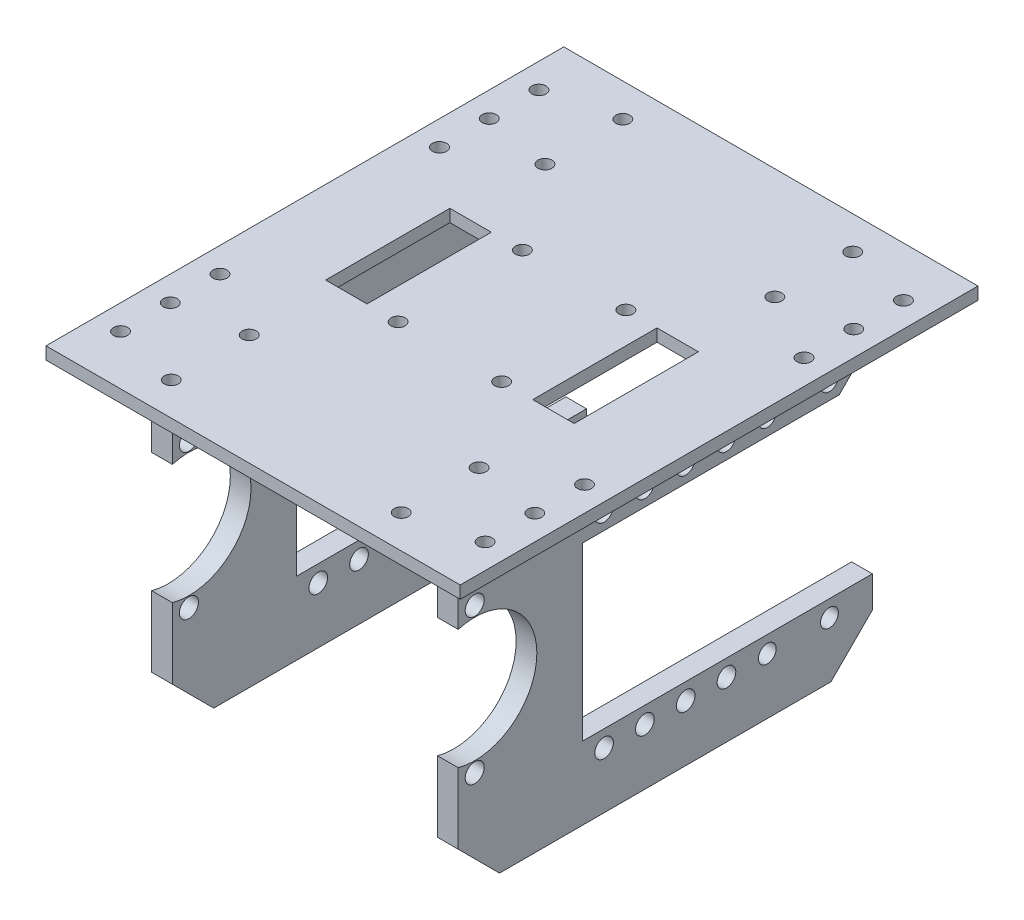
SolidWorks part; units mm, degrees
ref_plane "前视基准面" through (0, 0, 0) normal (0, 0, 1) x (1, 0, 0)
ref_plane "上视基准面" through (0, 0, 0) normal (0, 1, 0) x (1, 0, 0)
ref_plane "右视基准面" through (0, 0, 0) normal (1, 0, 0) x (0, 0, -1)
sketch "草图1" plane through (0, 0, 0) normal (0, 1, 0) x (1, 0, 0)
  line L1 (-50, -62.5) -> (50, -62.5)
  line L2 (-50, -62.5) -> (-50, 62.5)
  line L3 (-50, 62.5) -> (50, 62.5)
  line L4 (50, -62.5) -> (50, 62.5)
  line L5 (-50, -62.5) -> (50, 62.5) construction
  line L6 (-50, 62.5) -> (50, -62.5) construction
  point P0 (0, 0)
  dimension "D1" = 100
  dimension "D2" = 125
extrude "凸台-拉伸1" add sketch "草图1" along normal blind 3
sketch "草图2" plane through (0, 0, 0) normal (0, -1, 0) x (1, 0, 0)
  line L5 (0, -1.65) -> (0, 1.65) construction
  line L6 (-37, -50) -> (-32, -50)
  line L7 (-37, -50) -> (-37, 50)
  line L8 (-37, 50) -> (-32, 50)
  line L13 (-32, -50) -> (-32, 50)
  line L14 (-37, -50) -> (-32, 50) construction
  line L15 (-37, 50) -> (-32, -50) construction
  line L16 (37, 50) -> (32, -50) construction
  line L17 (37, -50) -> (32, 50) construction
  line L18 (32, -50) -> (32, 50)
  line L19 (37, 50) -> (32, 50)
  line L20 (37, -50) -> (37, 50)
  line L21 (37, -50) -> (32, -50)
  point P0 (-34.5, 0)
  point P11 (34.5, 0)
  dimension "D1" = 5
  dimension "D2" = 64
  dimension "D3" = 100
extrude "凸台-拉伸2" add sketch "草图2" along normal blind 75
sketch "草图3" plane through (-37, 0, 0) normal (-1, 0, 0) x (0, 0, 1)
  line L0 (0, -42.9) -> (0, 42.9) construction
  line L1 (50, 0) -> (-50, 0) construction
  line L2 (4.925, -12) -> (4.925, -61.42) construction
  line L3 (4.925, -36.71) -> (59.1857, -36.71) construction
  circle A0 centre (-4.925, -12) radius 2.25
  circle A1 centre (4.925, -12) radius 2.25
  circle A3 centre (-4.925, -61.42) radius 2.25
  circle A4 centre (4.925, -61.42) radius 2.25
  circle A5 centre (14.775, -12) radius 2.25
  circle A6 centre (14.775, -61.42) radius 2.25
  circle A7 centre (-14.775, -61.42) radius 2.25
  circle A8 centre (-14.775, -12) radius 2.25
  dimension "D1" = 9.85
  dimension "D2" = 12
  dimension "D3" = 2
  dimension "D4" = 9.85
  dimension "D5" = 4.5
  dimension "D6" = 4.5
extrude "切除-拉伸1" cut sketch "草图3" against normal blind 85
sketch "草图4" plane through (-37, 0, 0) normal (-1, 0, 0) x (0, 0, 1)
  line L2 (-20, -57.42) -> (20, -57.42)
  line L3 (-20, -57.42) -> (-20, -16)
  line L4 (-20, -16) -> (20, -16)
  line L5 (20, -57.42) -> (20, -16)
  line L6 (-20, -57.42) -> (20, -16) construction
  line L7 (-20, -16) -> (20, -57.42) construction
  circle A3 centre (-4.925, -12) radius 2.25 construction
  circle A4 centre (-4.925, -61.42) radius 2.25 construction
  point P4 (0, -36.71)
  dimension "D2" = 4
  dimension "D1" = 4
  dimension "D3" = 40
extrude "切除-拉伸2" cut sketch "草图4" against normal blind 85
chamfer "倒角1" distance 10 angle 45 4 edges at (34.5, -75, 50) (-34.5, -75, 50) (34.5, -75, -50) (-34.5, -75, -50)
sketch "草图5" plane through (0, 3, 0) normal (0, 1, 0) x (1, 0, 0)
  line L0 (0, -42.9) -> (0, 42.9) construction
  line L1 (-30, -15) -> (-20, -15)
  line L2 (-30, -15) -> (-30, 15)
  line L3 (-30, 15) -> (-20, 15)
  line L4 (-20, -15) -> (-20, 15)
  line L5 (-30, -15) -> (-20, 15) construction
  line L6 (-30, 15) -> (-20, -15) construction
  line L7 (30, 15) -> (20, -15) construction
  line L8 (30, -15) -> (20, 15) construction
  line L9 (20, -15) -> (20, 15)
  line L10 (30, 15) -> (20, 15)
  line L11 (30, -15) -> (30, 15)
  line L12 (30, -15) -> (20, -15)
  point P0 (-25, 0)
  point P11 (25, 0)
  dimension "D1" = 10
  dimension "D2" = 40
  dimension "D3" = 30
extrude "切除-拉伸3" cut sketch "草图5" against normal blind 85
ref_plane "基准面4" through (0, 23, 0) normal (0, 1, 0) x (1, 0, 0)
sketch "草图11" plane through (0, 0, 0) normal (0, -1, 0) x (1, 0, 0)
  line L0 (-50, -62.5) -> (-50, 62.5) construction
  line L1 (-50, 62.5) -> (50, 62.5) construction
  line L2 (0, -42.9) -> (0, 42.9) construction
  line L3 (42.9, 0) -> (-42.9, 0) construction
  circle A0 centre (-44, 50.5) radius 1.7
  circle A1 centre (-44, 38.5) radius 1.7
  circle A2 centre (-44, 26.5) radius 1.7
  circle A3 centre (44, 26.5) radius 1.7
  circle A4 centre (44, 38.5) radius 1.7
  circle A5 centre (44, 50.5) radius 1.7
  circle A6 centre (44, -50.5) radius 1.7
  circle A7 centre (44, -38.5) radius 1.7
  circle A8 centre (44, -26.5) radius 1.7
  circle A9 centre (-44, -26.5) radius 1.7
  circle A10 centre (-44, -38.5) radius 1.7
  circle A11 centre (-44, -50.5) radius 1.7
  dimension "D1" = 3.4
  dimension "D2" = 6
  dimension "D3" = 12
  dimension "D4" = 3
extrude "切除-拉伸5" cut sketch "草图11" against normal blind 10
sketch "草图12" plane through (0, 3, 0) normal (0, 1, 0) x (1, 0, 0)
  line L1 (0, -42.9) -> (0, 42.9) construction
  line L2 (50, 62.5) -> (-50, 62.5) construction
  line L3 (-42.9, 0) -> (42.9, 0) construction
  circle A0 centre (-27.75, 54.5) radius 1.7
  circle A2 centre (-27.75, 35.7) radius 1.7
  circle A3 centre (27.75, 35.7) radius 1.7
  circle A4 centre (27.75, 54.5) radius 1.7
  circle A5 centre (27.75, -54.5) radius 1.7
  circle A6 centre (27.75, -35.7) radius 1.7
  circle A7 centre (-27.75, -35.7) radius 1.7
  circle A8 centre (-27.75, -54.5) radius 1.7
  dimension "D1" = 18.8
  dimension "D2" = 3.4
  dimension "D3" = 3.4
  dimension "D4" = 55.5
  dimension "D5" = 8
extrude "切除-拉伸6" cut sketch "草图12" against normal blind 25
sketch "草图13" plane through (-37, 0, 0) normal (-1, 0, 0) x (0, 0, 1)
  line L0 (50, -65) -> (50, 0) construction
  line L1 (50, 0) -> (-50, 0) construction
  line L3 (46, -16) -> (46, -51) construction
  circle A0 centre (46, -16) radius 2.3
  circle A1 centre (46, -51) radius 2.3
  circle A4 centre (46, -33.5) radius 15
  dimension "D1" = 35
  dimension "D2" = 4.6
  dimension "D3" = 4.6
  dimension "D4" = 4
  dimension "D5" = 16
  dimension "D6" = 30
extrude "切除-拉伸9" cut sketch "草图13" against normal blind 105
sketch "草图14" plane through (-37, 0, 0) normal (-1, 0, 0) x (0, 0, 1)
  line L0 (-20, -57.42) -> (20, -57.42) construction
  line L1 (-20, -16) -> (-35, -16)
  line L2 (-20, -16) -> (-20, -57.42)
  line L3 (-20, -57.42) -> (-35, -57.42)
  line L4 (-35, -16) -> (-35, -57.42)
  dimension "D1" = 15
extrude "切除-拉伸10" cut sketch "草图14" against normal blind 83
sketch "草图15" plane through (-37, 0, 0) normal (-1, 0, 0) x (0, 0, 1)
  line L0 (-35, -16) -> (-35, -57.42) construction
  line L1 (-15.5119, -57.42) -> (-54.4881, -57.42)
  line L2 (-15.5119, -57.42) -> (-15.5119, -16)
  line L3 (-15.5119, -16) -> (-54.4881, -16)
  line L4 (-54.4881, -57.42) -> (-54.4881, -16)
  line L5 (-15.5119, -57.42) -> (-54.4881, -16) construction
  line L6 (-15.5119, -16) -> (-54.4881, -57.42) construction
  line L7 (-35, -57.42) -> (20, -57.42) construction
  point P0 (-35, -36.71)
  point P7 (-30, -56.71)
  point P8 (-30, -56.71)
  point P9 (-30, -57.42)
extrude "切除-拉伸11" cut sketch "草图15" against normal blind 83
sketch "草图16" plane through (0, 3, 0) normal (0, 1, 0) x (1, 0, 0)
  line L0 (0, -42.9) -> (0, 42.9) construction
  line L1 (-42.9, 0) -> (42.9, 0) construction
  circle A0 centre (-12.5, 15) radius 1.7
  circle A1 centre (12.5, 15) radius 1.7
  circle A2 centre (12.5, -15) radius 1.7
  circle A3 centre (-12.5, -15) radius 1.7
  dimension "D1" = 3.4
  dimension "D2" = 25
  dimension "D3" = 30
extrude "切除-拉伸12" cut sketch "草图16" against normal blind 83
sketch "草图17" plane through (-37, 0, 0) normal (-1, 0, 0) x (0, 0, 1)
  line L0 (20, -36.71) -> (2.0906, -36.71) construction
  line L2 (20, -57.42) -> (20, -16) construction
  circle A0 centre (-24.625, -12) radius 2.15
  circle A1 centre (-14.775, -12) radius 2.25 construction
  circle A2 centre (-24.625, -61.42) radius 2.15
  circle A3 centre (-39.625, -12) radius 2.15
  circle A4 centre (-39.625, -61.42) radius 2.15
  point P4 (-14.775, -12)
  dimension "D1" = 9.85
  dimension "D2" = 4.3
  dimension "D3" = 4.3
  dimension "D4" = 15
extrude "切除-拉伸13" cut sketch "草图17" against normal blind 83
chamfer "倒角2" distance 8 angle 45 2 edges at (34.5, -16, -50) (-34.5, -16, -50)
